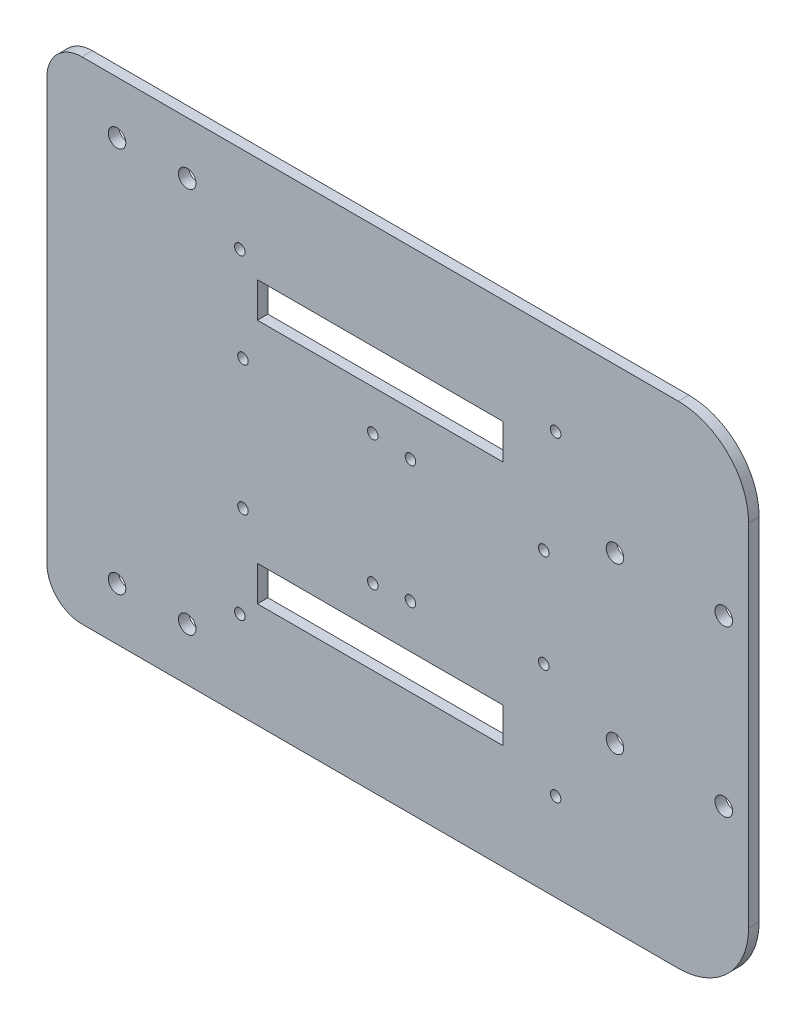
SolidWorks part; units mm, degrees
ref_plane "Front Plane" through (0, 0, 0) normal (0, 0, 1) x (1, 0, 0)
ref_plane "Top Plane" through (0, 0, 0) normal (0, 1, 0) x (1, 0, 0)
ref_plane "Right Plane" through (0, 0, 0) normal (1, 0, 0) x (0, 0, -1)
sketch "Sketch1" plane through (0, 0, 0) normal (0, 0, 1) x (1, 0, 0)
  line L1 (-100, 70) -> (100, 70)
  line L2 (-100, 70) -> (-100, -70)
  line L3 (-100, -70) -> (100, -70)
  line L4 (100, 70) -> (100, -70)
  line L5 (-100, 70) -> (100, -70) construction
  line L6 (-100, -70) -> (100, 70) construction
  point P0 (0, 0)
  dimension "D1" = 200
  dimension "D2" = 140
extrude "Boss-Extrude1" add sketch "Sketch1" along normal blind 3
sketch "Sketch2" plane through (0, 0, 3) normal (0, 0, 1) x (1, 0, 0)
  line L0 (-100, -70) -> (100, -70) construction
  line L1 (-80, -70) -> (-60, -70) construction
  line L2 (-80, -70) -> (-80, -55) construction
  line L3 (-80, -55) -> (-60, -55) construction
  line L4 (-60, -70) -> (-60, -55) construction
  line L5 (3.6211, -17.5) -> (3.6211, 17.5) construction
  line L10 (-100, 0) -> (100, 0) construction
  line L11 (-100, 70) -> (-100, -70) construction
  line L12 (100, -70) -> (100, 70) construction
  line L13 (-60, 70) -> (-60, 55) construction
  line L14 (-80, 55) -> (-60, 55) construction
  line L15 (-80, 70) -> (-80, 55) construction
  line L16 (-80, 70) -> (-60, 70) construction
  line L17 (-40, 40) -> (30, 40)
  line L18 (61.917, 23.5) -> (92.917, 23.5) construction
  line L19 (61.917, 23.5) -> (61.917, -23.5) construction
  line L20 (61.917, -23.5) -> (92.917, -23.5) construction
  line L21 (92.917, 23.5) -> (92.917, -23.5) construction
  line L22 (61.917, 23.5) -> (92.917, -23.5) construction
  line L23 (61.917, -23.5) -> (92.917, 23.5) construction
  line L28 (-44.1119, 18.5) -> (-7.1119, 18.5) construction
  line L29 (-44.1119, 18.5) -> (-44.1119, -18.5) construction
  line L30 (3.6211, 14) -> (41.6211, 14) construction
  line L31 (3.6211, 14) -> (3.6211, -14)
  line L32 (3.6211, -14) -> (41.6211, -14) construction
  line L33 (41.6211, 14) -> (41.6211, -14) construction
  line L34 (3.6211, 14) -> (41.6211, -14) construction
  line L35 (3.6211, -14) -> (41.6211, 14) construction
  line L36 (-44.1119, -18.5) -> (-7.1119, -18.5) construction
  line L37 (-7.1119, 18.5) -> (-7.1119, -18.5) construction
  line L38 (-44.1119, 18.5) -> (-7.1119, -18.5) construction
  line L39 (-44.1119, -18.5) -> (-7.1119, 18.5) construction
  line L40 (-40, -30) -> (30, -30)
  line L41 (-40, -30) -> (-40, -40)
  line L42 (-40, -40) -> (30, -40)
  line L43 (30, -30) -> (30, -40)
  line L48 (30, 30) -> (30, 40)
  line L49 (-40, 30) -> (30, 30)
  line L50 (-40, 30) -> (-40, 40)
  line L52 (-45, 45) -> (45, 45)
  line L53 (-45, 45) -> (-45, -45)
  line L54 (-45, -45) -> (45, -45)
  line L55 (45, 45) -> (45, -45)
  line L56 (-45, 45) -> (45, -45) construction
  line L57 (-45, -45) -> (45, 45) construction
  circle A0 centre (-60, -55) radius 2.5
  circle A1 centre (-80, -55) radius 2.5
  circle A2 centre (-80, 55) radius 2.5
  circle A3 centre (-60, 55) radius 2.5
  circle A4 centre (61.917, 23.5) radius 2.5
  circle A5 centre (92.917, 23.5) radius 2.5
  circle A6 centre (92.917, -23.5) radius 2.5
  circle A7 centre (61.917, -23.5) radius 2.5
  circle A8 centre (41.6211, 14) radius 1.5
  circle A9 centre (41.6211, -14) radius 1.5
  circle A10 centre (3.6211, 17.5) radius 1.5
  circle A11 centre (3.6211, -17.5) radius 1.5
  circle A12 centre (-44.1119, 18.5) radius 1.5
  circle A13 centre (-7.1119, 18.5) radius 1.5
  circle A14 centre (-7.1119, -18.5) radius 1.5
  circle A15 centre (-44.1119, -18.5) radius 1.5
  circle A16 centre (45, 45) radius 1.5
  circle A17 centre (45, -45) radius 1.5
  circle A18 centre (-45, -45) radius 1.5
  circle A19 centre (-45, 45) radius 1.5
  point P6 (77.417, 0)
  point P30 (18.5, 0)
  point P31 (-25.6119, 0)
  point P35 (22.6211, 0)
  point P45 (3.6211, 0)
  point P56 (0, 0)
  dimension "D3" = 5
  dimension "D7" = 5
  dimension "D13" = 3
  dimension "D10" = 3
  dimension "D21" = 3
  dimension "D1" = 15
  dimension "D2" = 20
  dimension "D4" = 20
  dimension "D5" = 47
  dimension "D6" = 31
  dimension "D8" = 37
  dimension "D9" = 37
  dimension "D11" = 28
  dimension "D12" = 35
  dimension "D14" = 38
  dimension "D15" = 30
  dimension "D16" = 10
  dimension "D17" = 60
  dimension "D18" = 70
  dimension "D19" = 90
  dimension "D20" = 90
extrude "Cut-Extrude1" cut sketch "Sketch2" against normal up to surface (3 mm away) contours A11 | A8 | A12 | A13 | A14 | A7 | A6 | A5 | A4 | A3 | A0 | A1 | L55 A16 L52 | L52 A16 L55 | L50 L49 L48 L17 | L53 A19 L52 | L52 A19 L53 | L53 A15 | L53 A15 | A9 | A2 | L41 L40 L43 L42 | A17 | A18 | A10 up to face at (0, 0, 0)
fillet "Fillet1" radius 10 2 edges at (-100, 70, 1.5) (-100, -70, 1.5)
fillet "Fillet2" radius 20 2 edges at (100, 70, 1.5) (100, -70, 1.5)
equation "\"`100\"=60"
